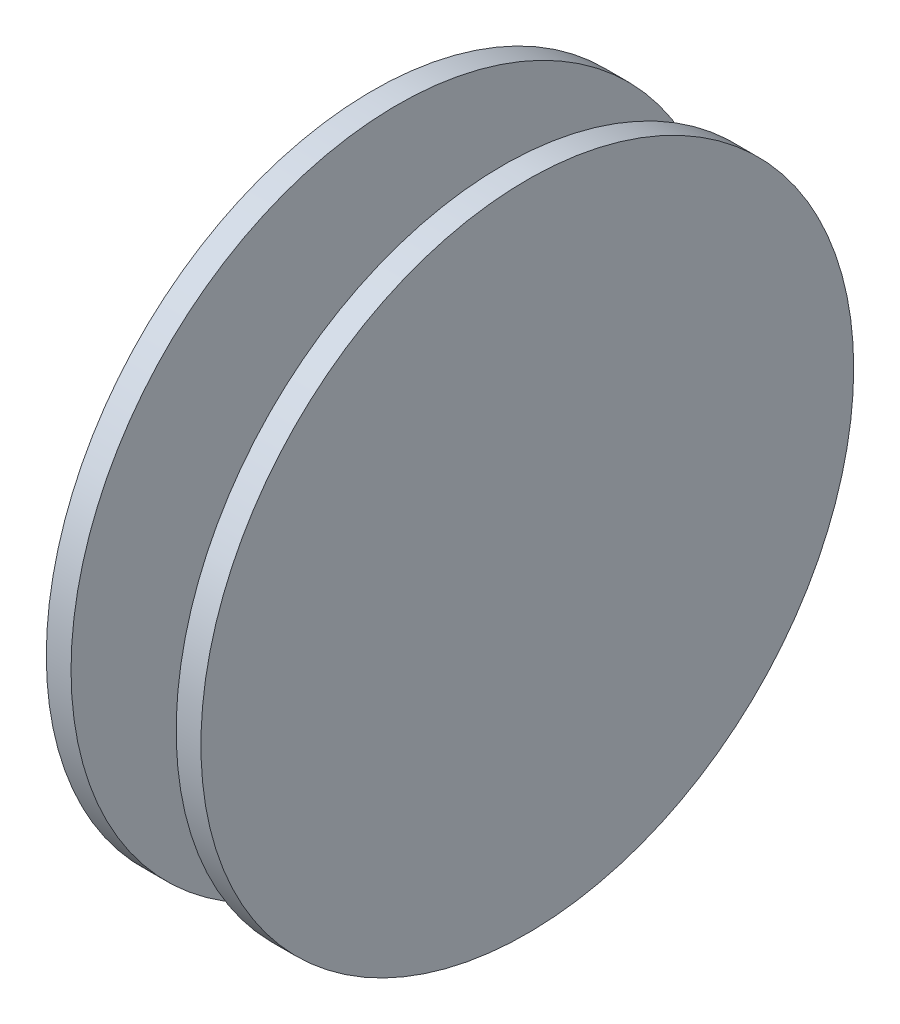
SolidWorks part; units mm, degrees
ref_plane "Front Plane" through (0, 0, 0) normal (0, 0, 1) x (1, 0, 0)
ref_plane "Top Plane" through (0, 0, 0) normal (0, 1, 0) x (1, 0, 0)
ref_plane "Right Plane" through (0, 0, 0) normal (1, 0, 0) x (0, 0, -1)
sketch "Sketch4" plane through (0, 0, 0) normal (1, 0, 0) x (0, 0, -1)
  circle A0 centre (0, 0) radius 83.82
extrude "Boss-Extrude1" add sketch "Sketch4" along normal blind 6.35 contours A0
sketch "Sketch5" plane through (0, 0, 0) normal (-1, 0, 0) x (0, 0, 1)
  circle A0 centre (0, 0) radius 5
extrude "Boss-Extrude4" add sketch "Sketch5" along normal blind 27
sketch "Sketch7" plane through (-27, 0, 0) normal (-1, 0, 0) x (0, 0, 1)
  circle A0 centre (0, 0) radius 83.82
extrude "Boss-Extrude5" add sketch "Sketch7" along normal blind 6.35
